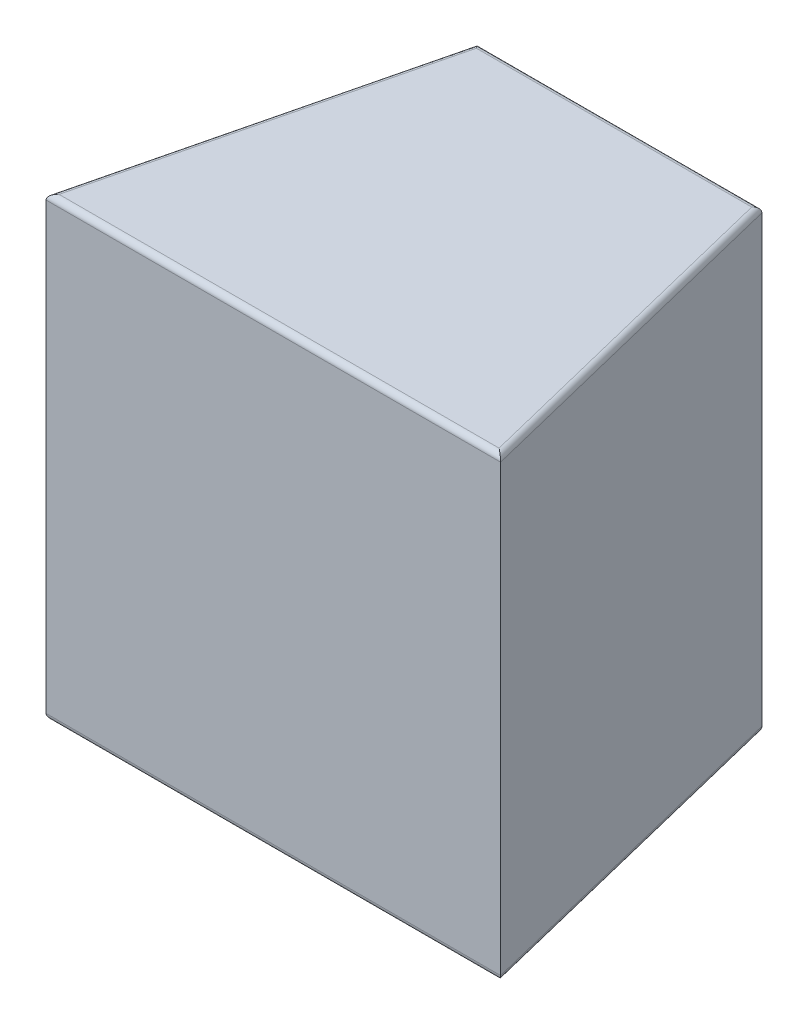
SolidWorks part; units mm, degrees
ref_plane "Front Plane" through (0, 0, 0) normal (1, 0, 0) x (0, 1, 0)
ref_plane "Top Plane" through (0, 0, 0) normal (0, 0, 1) x (0, 1, 0)
ref_plane "Right Plane" through (0, 0, 0) normal (0, 1, 0) x (-1, 0, 0)
sketch "Sketch1" plane through (0, 0, 0) normal (0, 1, 0) x (-1, 0, 0)
  line L0 (-19.9299, 15.2829) -> (19.92, 15.3046)
  line L1 (19.92, 15.3046) -> (12.4774, -15.0994)
  line L2 (12.4774, -15.0994) -> (-12.4541, -15.113)
  line L3 (-12.4541, -15.113) -> (-19.9299, 15.2829)
extrude "Boss-Extrude1" add sketch "Sketch1" along normal blind 40
fillet "Fillet1" radius 0.5 8 edges at (16.192, 0, 0.085) (-0.0116, 0, -15.1062) (-16.1987, 0, 0.1026) (0.0049, 0, 15.2938) (16.192, 40, 0.085) (-0.0116, 40, -15.1062) (-16.1987, 40, 0.1026) (0.0049, 40, 15.2938)
